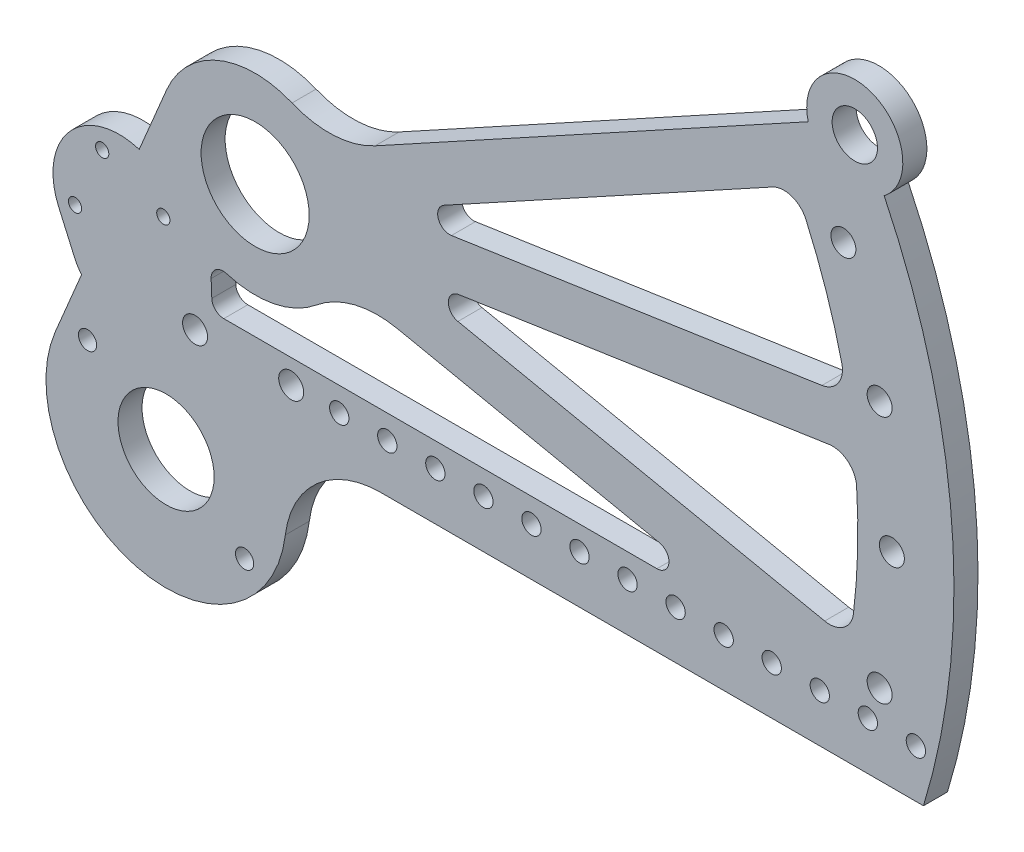
SolidWorks part; units mm, degrees
material "6061-T6 (SS)"
ref_plane "Front Plane" through (0, 0, 0) normal (0, 0, 1) x (1, 0, 0)
ref_plane "Top Plane" through (0, 0, 0) normal (0, 1, 0) x (1, 0, 0)
ref_plane "Right Plane" through (0, 0, 0) normal (1, 0, 0) x (0, 0, -1)
ref_plane "Plane1" through (0, 0, 0) normal (0, 0, -1) x (-1, 0, 0)
sketch "Sketch1" plane through (0, 0, 0) normal (0, 0, -1) x (-1, 0, 0)
  line L0 (-136.7019, 67.6925) -> (-49.8885, 20.1052)
  line L1 (-51.8843, 14.181) -> (-149.7957, 28.8257)
  line L2 (-106.8353, -28.6411) -> (-37.5401, -14.2704)
  line L3 (11.6318, -27.4189) -> (11.4566, -31.8747)
  line L4 (8.2841, -34.925) -> (-106.1906, -34.925)
  line L5 (-151.6743, 16.2654) -> (-53.7629, 1.6207)
  line L6 (-53.5879, -4.6282) -> (-150.5258, -24.7317)
  line L7 (-31.7217, 24.6299) -> (-146.1701, 87.3654)
  line L8 (-176.627, -53.975) -> (-33.1944, -53.975)
  line L9 (52.8124, -60.1841) -> (45.8592, -43.6206)
  line L10 (47.5699, -41.0132) -> (51.9346, -31.1397)
  line L11 (30.6457, -7.3807) -> (23.42, 9.8317)
  circle A0 centre (40.4212, -12.3994) radius 1.75
  circle A1 centre (47.5935, -28.5567) radius 1.75
  circle A2 centre (15.875, -41.275) radius 3.302
  circle A3 centre (2.7815, -87.1145) radius 2.413
  circle A4 centre (44.2932, -57.8328) radius 2.413
  circle A5 centre (23.5374, -72.4737) radius 12.7
  circle A6 centre (-9.525, -41.275) radius 3.302
  arc A7 (-145.5567, 64.7035) -> (-136.7019, 67.6925) centre (-139.7541, 62.1242) cw
  arc A8 (-49.8885, 20.1052) -> (-51.8843, 14.181) centre (-51.4146, 17.3211) cw
  arc A9 (-149.7957, 28.8257) -> (-155.0368, 36.5634) centre (-148.8564, 35.1058) cw
  arc A10 (-155.0368, 36.5634) -> (-145.5567, 64.7035) centre (0, 0) cw
  circle A11 centre (-165.0416, 32.8288) radius 3.302
  circle A12 centre (-165.0416, -32.8288) radius 3.302
  arc A13 (-106.1906, -34.925) -> (-106.8353, -28.6411) centre (-106.1906, -31.75) cw
  arc A14 (-37.5401, -14.2704) -> (-16.1911, -19.5706) centre (-32.3822, -39.1412) cw
  arc A15 (-16.1911, -19.5706) -> (7.5193, -24.2615) centre (0, 0) ccw
  arc A16 (7.5193, -24.2615) -> (11.6318, -27.4189) centre (8.4593, -27.2942) cw
  arc A17 (11.4566, -31.8747) -> (8.2841, -34.925) centre (8.2841, -31.75) cw
  arc A18 (-158.9501, 10.3998) -> (-151.6743, 16.2654) centre (-152.6137, 9.9852) cw
  arc A19 (-53.7629, 1.6207) -> (-53.5879, -4.6282) centre (-54.2326, -1.5194) cw
  arc A20 (-150.5258, -24.7317) -> (-158.1185, -19.2827) centre (-151.8152, -18.514) cw
  arc A21 (-158.1185, -19.2827) -> (-158.9501, 10.3998) centre (0, 0) cw
  circle A22 centre (-155.4658, 64.3961) radius 3.302
  circle A23 centre (-168.275, 0) radius 3.302
  circle A24 centre (0, 0) radius 14.2811
  circle A25 centre (-174.625, -41.275) radius 2.5527
  circle A26 centre (-161.925, -41.275) radius 2.5527
  circle A27 centre (-149.225, -41.275) radius 2.5527
  circle A28 centre (-136.525, -41.275) radius 2.5527
  circle A29 centre (-123.825, -41.275) radius 2.5527
  circle A30 centre (-111.125, -41.275) radius 2.5527
  circle A31 centre (-98.425, -41.275) radius 2.5527
  circle A32 centre (-73.025, -41.275) radius 2.5527
  circle A33 centre (-85.725, -41.275) radius 2.5527
  circle A34 centre (-60.325, -41.275) radius 2.5527
  circle A35 centre (-47.625, -41.275) radius 2.5527
  circle A36 centre (-34.925, -41.275) radius 2.5527
  circle A37 centre (-22.225, -41.275) radius 2.5527
  circle A38 centre (24.2639, -19.5717) radius 1.75
  circle A39 centre (-158.4749, 90.5087) radius 5.9944
  arc A40 (-146.1701, 87.3654) -> (-166.2421, 80.4608) centre (-158.4749, 90.5087) ccw
  arc A41 (-166.2421, 80.4608) -> (-176.627, -53.975) centre (0, 0) ccw
  arc A42 (-33.1944, -53.975) -> (-7.9803, -76.3077) centre (-33.1944, -79.375) cw
  arc A43 (-7.9803, -76.3077) -> (52.8124, -60.1841) centre (23.5374, -72.4737) ccw
  arc A44 (45.8592, -43.6206) -> (47.5699, -41.0132) centre (38.8582, -37.1622) ccw
  arc A45 (51.9346, -31.1397) -> (30.6457, -7.3807) centre (35.9287, -24.0642) ccw
  arc A46 (23.42, 9.8317) -> (-9.7563, 23.4515) centre (0, 0) ccw
  arc A47 (-9.7563, 23.4515) -> (-31.7217, 24.6299) centre (-19.5126, 46.9031) cw
extrude "Boss-Extrude1" add sketch "Sketch1" against normal blind 6.35
